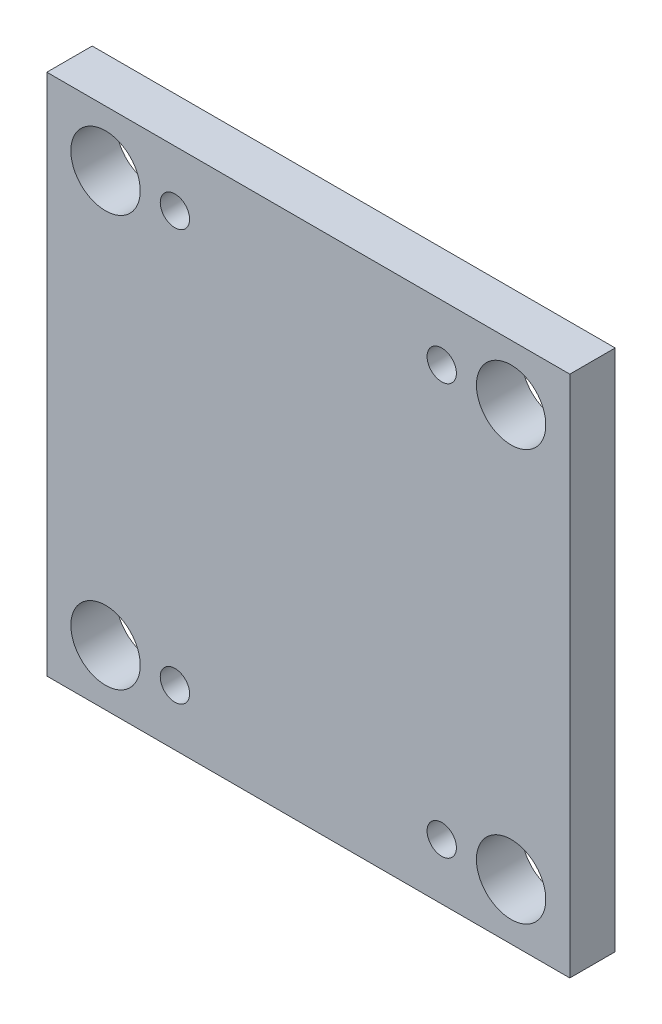
SolidWorks part; units mm, degrees
ref_plane "Спереди" through (0, 0, 0) normal (0, 0, 1) x (1, 0, 0)
ref_plane "Сверху" through (0, 0, 0) normal (0, 1, 0) x (1, 0, 0)
ref_plane "Справа" through (0, 0, 0) normal (1, 0, 0) x (0, 0, -1)
ref_plane "Плоскость4" through (0, 0, 17) normal (0, 0, 1) x (1, 0, 0)
sketch "Эскиз1" plane through (0, 0, 17) normal (0, 0, 1) x (1, 0, 0)
  line L0 (98, 98) -> (-98, 98)
  line L1 (-98, 98) -> (-98, -98)
  line L2 (-98, -98) -> (98, -98)
  line L3 (98, -98) -> (98, 98)
  circle A0 centre (-50, -77) radius 5.5
  circle A1 centre (-50, 76.9999) radius 5.5
  circle A2 centre (50, -77) radius 5.5
  circle A3 centre (50, 76.9999) radius 5.5
  circle A4 centre (-76, 77) radius 13
  circle A5 centre (-76, -77) radius 13
  circle A6 centre (76, -77) radius 13
  circle A7 centre (76, 77) radius 13
extrude "Бобышка-Вытянуть1" add sketch "Эскиз1" against normal blind 17
